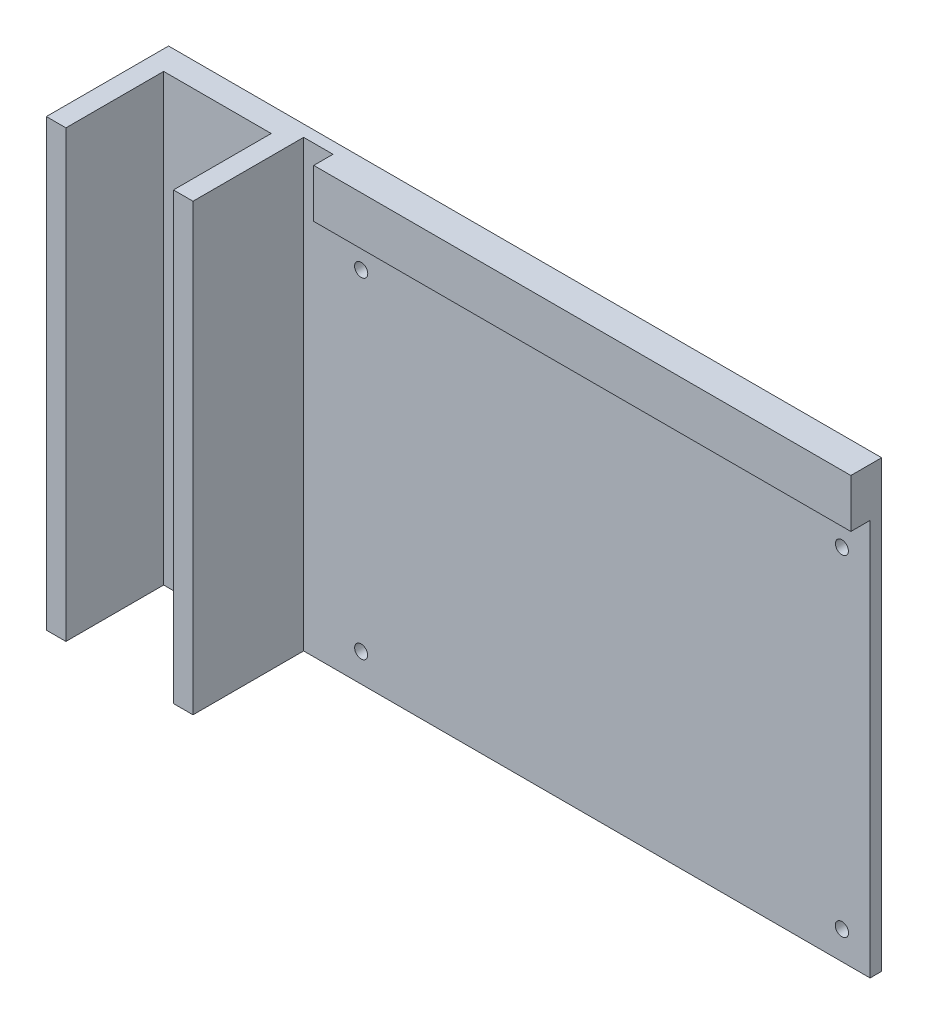
SolidWorks part; units mm, degrees
ref_plane "Front Plane" through (0, 0, 0) normal (0, 0, 1) x (1, 0, 0)
ref_plane "Top Plane" through (0, 0, 0) normal (0, 1, 0) x (1, 0, 0)
ref_plane "Right Plane" through (0, 0, 0) normal (1, 0, 0) x (0, 0, -1)
sketch "Sketch2" plane through (0, 0, 0) normal (0, 0, 1) x (1, 0, 0)
  line L1 (-69.7742, 52.705) -> (69.7742, 52.705)
  line L2 (-69.7742, 52.705) -> (-69.7742, -53.975)
  line L3 (-69.7742, -53.975) -> (69.7742, -53.975)
  line L4 (69.7742, 52.705) -> (69.7742, -53.975)
  circle A0 centre (-62.4579, -46.6153) radius 1.6944
  circle A1 centre (62.4455, -46.6473) radius 1.7265
  circle A2 centre (62.4492, 39.2742) radius 1.6916
  circle A4 centre (-62.4507, 39.2536) radius 1.7118
  dimension "D1" = 106.68
extrude "Boss-Extrude1" add sketch "Sketch2" along normal blind 3
sketch "Sketch3" plane through (0, 0, 3) normal (0, 0, 1) x (1, 0, 0)
  line L0 (69.7742, -53.975) -> (69.7742, 52.705) construction
  line L1 (-69.7742, 52.705) -> (69.7742, 52.705)
  line L2 (-69.7742, 52.705) -> (-69.7742, 48.9936)
  line L3 (-69.7742, 48.9936) -> (69.7742, 48.9936)
  line L4 (69.7742, 52.705) -> (69.7742, 48.9936)
extrude "Boss-Extrude3" add sketch "Sketch3" along normal blind 5
sketch "Sketch5" plane through (0, 52.705, 0) normal (0, 1, 0) x (1, 0, 0)
  line L1 (-69.7742, -8) -> (69.7742, -8)
  line L2 (-69.7742, -8) -> (-69.7742, 0)
  line L3 (-69.7742, 0) -> (69.7742, 0)
  line L4 (69.7742, -8) -> (69.7742, 0)
extrude "Boss-Extrude4" add sketch "Sketch5" along normal blind 8.89
sketch "Sketch6" plane through (0, 0, 0) normal (0, 0, -1) x (-1, 0, 0)
  line L0 (69.7742, -53.975) -> (69.7742, 61.595)
  line L1 (69.7742, -53.975) -> (114.2242, -53.975)
  line L2 (69.7742, 61.595) -> (114.2242, 61.595)
  line L3 (114.2242, -53.975) -> (114.2242, 61.595)
  line L4 (114.2242, -53.975) -> (114.2242, 61.595)
  line L5 (114.2242, -53.975) -> (76.1242, -53.975)
  line L6 (114.2242, 61.595) -> (76.1242, 61.595)
  line L7 (76.1242, -53.975) -> (76.1242, 61.595)
  dimension "D1" = 44.45
  dimension "D2" = 38.1
sketch "Sketch11" plane through (0, 0, 0) normal (0, 0, -1) x (-1, 0, 0)
  line L0 (69.7742, 61.595) -> (69.7742, -53.975)
  line L1 (69.7742, 61.595) -> (115.4942, 61.595)
  line L2 (69.7742, -53.975) -> (115.4942, -53.975)
  line L3 (115.4942, 61.595) -> (115.4942, -53.975)
  line L4 (115.4942, 61.595) -> (115.4942, -53.975)
  line L5 (115.4942, 61.595) -> (77.3942, 61.595)
  line L6 (115.4942, -53.975) -> (77.3942, -53.975)
  line L7 (77.3942, 61.595) -> (77.3942, -53.975)
  line M4 (69.7742, -53.975) -> (69.7742, 61.595)
  dimension "D1" = 45.72
  dimension "D2" = 38.1
extrude "Boss-Extrude6" add sketch "Sketch11" against normal up to surface (3 mm away) contours L7 L1 L2 M4 up to face at (0, -2.4907, 3)
sketch "Sketch12" plane through (0, 0, 0) normal (0, 0, -1) x (-1, 0, 0)
  line L0 (77.3942, 61.595) -> (77.3942, -53.975)
  line L1 (77.3942, 61.595) -> (115.4942, 61.595)
  line L2 (77.3942, -53.975) -> (115.4942, -53.975)
  line L3 (115.4942, 61.595) -> (115.4942, -53.975)
  dimension "D1" = 38.1
extrude "Boss-Extrude7" add sketch "Sketch12" against normal blind 31.75
sketch "Sketch13" plane through (0, 0, 31.75) normal (0, 0, 1) x (1, 0, 0)
  line L8 (-110.4142, -48.895) -> (-110.4142, -53.975)
  line L9 (-77.3942, -53.975) -> (-115.4942, -53.975) construction
  line L10 (-110.4142, -53.975) -> (-82.4742, -53.975)
  line L11 (-82.4742, -53.975) -> (-82.4742, -48.895)
  line L12 (-82.4742, 56.515) -> (-110.4142, 56.515)
  line L13 (-110.4142, 56.515) -> (-110.4142, -48.895)
  line L14 (-110.4142, -48.895) -> (-82.4742, -48.895)
  line L15 (-82.4742, -48.895) -> (-82.4742, 56.515)
  line L17 (-110.4142, 56.515) -> (-110.4142, -48.895)
  line L19 (-82.4742, -48.895) -> (-82.4742, 56.515)
  line L20 (-82.4742, 56.515) -> (-82.4742, 61.595)
  line L21 (-115.4942, 61.595) -> (-77.3942, 61.595) construction
  line L22 (-82.4742, 61.595) -> (-110.4142, 61.595)
  line L23 (-110.4142, 61.595) -> (-110.4142, 56.515)
  dimension "D1" = 5.08
extrude "Cut-Extrude5" cut sketch "Sketch13" against normal blind 25.4 contours L17 L8 L10 L11 L19 L20 L22 L23
